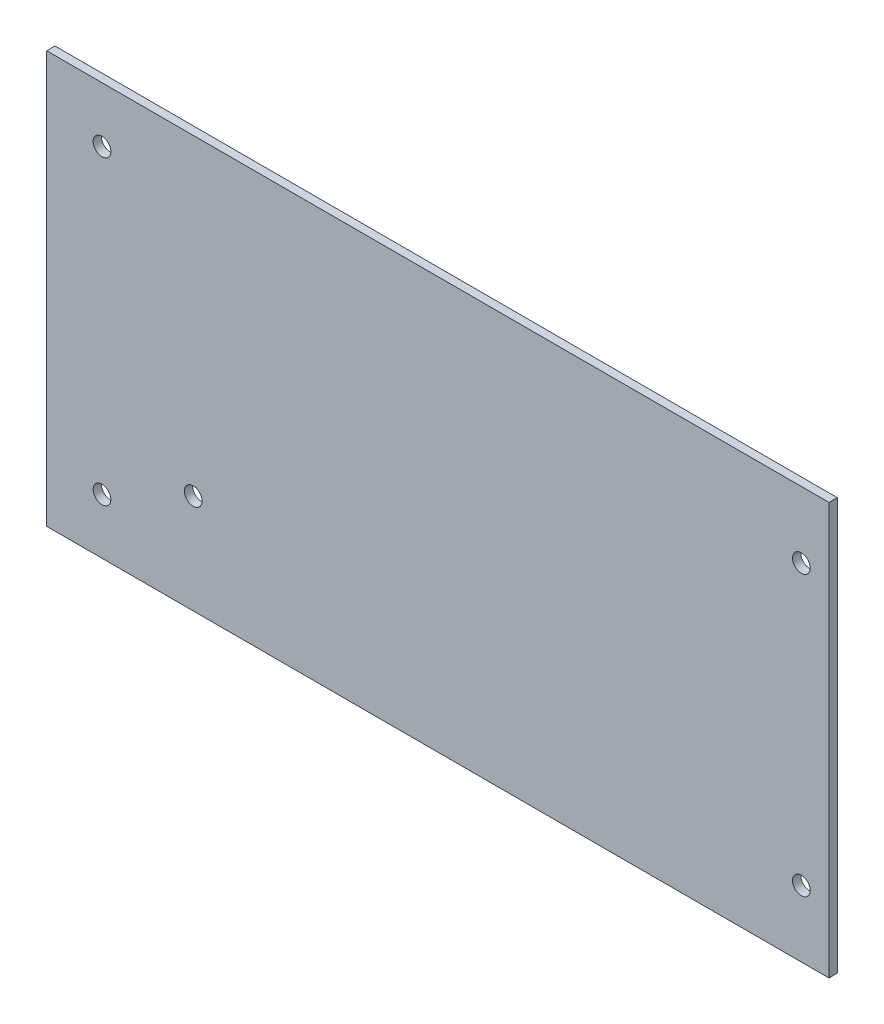
SolidWorks part; units mm, degrees
ref_plane "Front Plane" through (0, 0, 0) normal (0, 0, 1) x (1, 0, 0)
ref_plane "Top Plane" through (0, 0, 0) normal (0, 1, 0) x (1, 0, 0)
ref_plane "Right Plane" through (0, 0, 0) normal (1, 0, 0) x (0, 0, -1)
sketch "Sketch1" plane through (0, 0, 0) normal (0, 0, 1) x (1, 0, 0)
  line L1 (-69.9628, 74.5) -> (71.5372, 74.5)
  line L2 (-69.9628, 74.5) -> (-69.9628, 0)
  line L3 (-69.9628, 0) -> (71.5372, 0)
  line L4 (71.5372, 74.5) -> (71.5372, 0)
  dimension "D1" = 74.5
  dimension "D2" = 141.5
extrude "Boss-Extrude1" add sketch "Sketch1" along normal blind 1.5
sketch "Sketch2" plane through (0, 0, 1.5) normal (0, 0, 1) x (1, 0, 0)
  line L0 (-69.9628, 0) -> (71.5372, 0) construction
  line L1 (71.5372, 74.5) -> (-69.9628, 74.5) construction
  line L2 (-69.9628, 74.5) -> (-69.9628, 0) construction
  circle A0 centre (-59.9628, 64.5) radius 1.6
  circle A1 centre (-59.9628, 10) radius 1.6
  dimension "D1" = 3.2
  dimension "D2" = 3.2
  dimension "D3" = 10
  dimension "D4" = 10
  dimension "D5" = 10
  dimension "D6" = 10
extrude "Cut-Extrude1" cut sketch "Sketch2" against normal blind 1.5
sketch "Sketch3" plane through (0, 0, 1.5) normal (0, 0, 1) x (1, 0, 0)
  line L0 (71.5372, 74.5) -> (-69.9628, 74.5) construction
  line L1 (-69.9628, 0) -> (71.5372, 0) construction
  line L2 (71.5372, 0) -> (71.5372, 74.5) construction
  circle A0 centre (66.5372, 62.5) radius 1.6
  circle A1 centre (66.5372, 12) radius 1.6
  dimension "D1" = 3.2
  dimension "D2" = 3.2
  dimension "D3" = 12
  dimension "D4" = 12
  dimension "D5" = 5
  dimension "D6" = 5
extrude "Cut-Extrude2" cut sketch "Sketch3" against normal blind 1.5
sketch "Sketch4" plane through (0, 0, 1.5) normal (0, 0, 1) x (1, 0, 0)
  circle A0 centre (-43.4628, 18) radius 1.6
  dimension "D1" = 3.2
extrude "Cut-Extrude3" cut sketch "Sketch4" against normal blind 1.5
